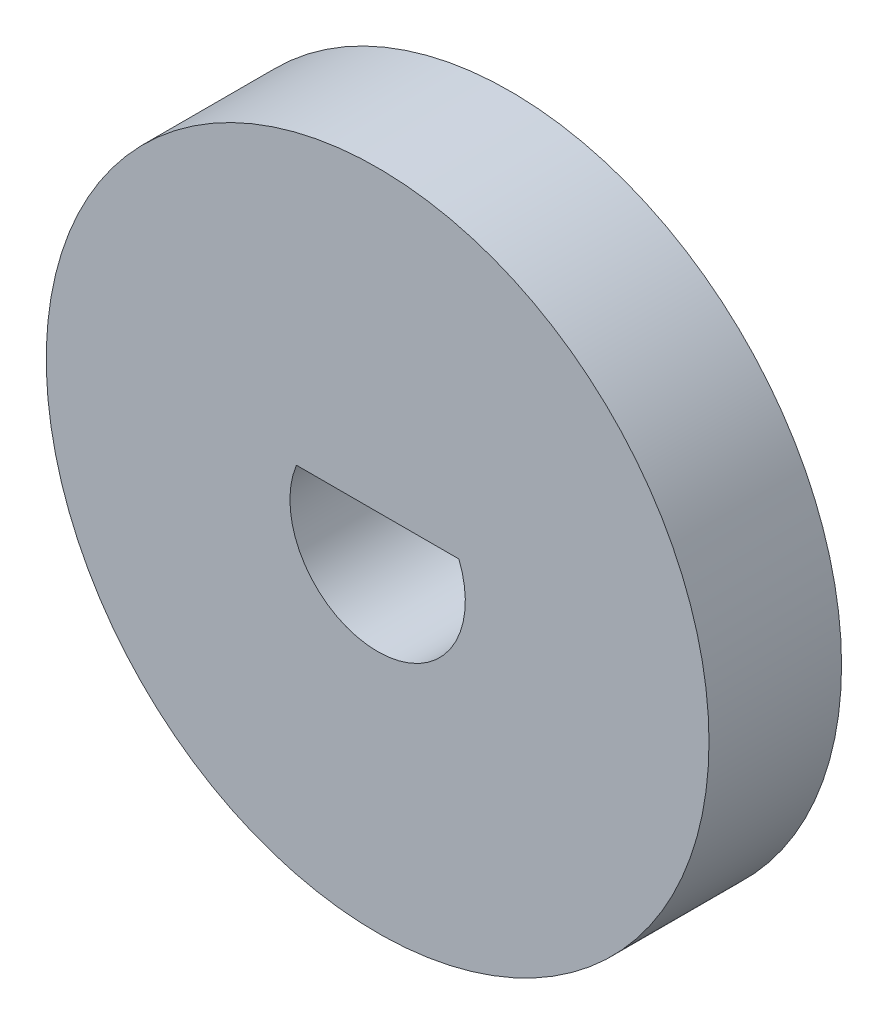
SolidWorks part; units mm, degrees
ref_plane "前视基准面" through (0, 0, 0) normal (0, 0, 1) x (1, 0, 0)
ref_plane "上视基准面" through (0, 0, 0) normal (0, 1, 0) x (1, 0, 0)
ref_plane "右视基准面" through (0, 0, 0) normal (1, 0, 0) x (0, 0, -1)
other "Configuration Table"
sketch "草图1" plane through (0, 0, 0) normal (0, 0, 1) x (1, 0, 0)
  line L0 (4.9, 2) -> (-4.9, 2)
  circle A0 centre (0, 0) radius 20
  arc A1 (-4.9, 2) -> (4.9, 2) centre (0, 0) ccw
extrude "凸台-拉伸1" add sketch "草图1" along normal blind 8
